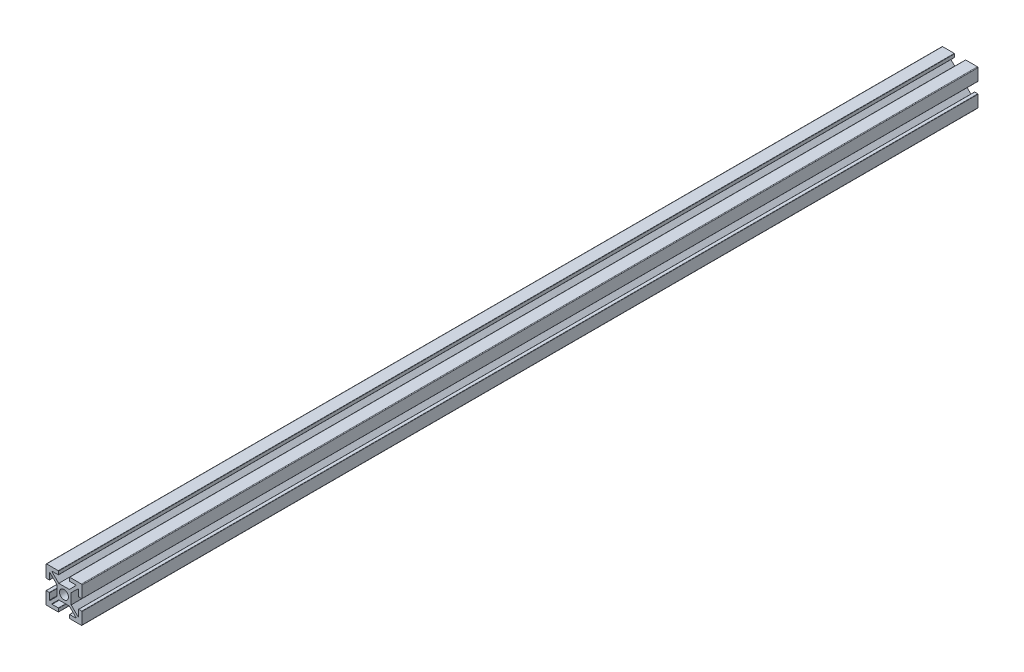
SolidWorks part; units mm, degrees
ref_plane "Front Plane" through (0, 0, 0) normal (0, 0, 1) x (1, 0, 0)
ref_plane "Top Plane" through (0, 0, 0) normal (0, 1, 0) x (1, 0, 0)
ref_plane "Right Plane" through (0, 0, 0) normal (1, 0, 0) x (0, 0, -1)
sketch "Sketch1" plane through (0, 0, 0) normal (0, 0, 1) x (1, 0, 0)
  line L0 (-7.4274, 2.1557) -> (-5.7274, 2.1557)
  line L1 (-0.7274, 9.1557) -> (-7.2274, 9.1557)
  line L2 (-7.5774, 2.3057) -> (-7.5774, 8.8057)
  line L3 (5.4021, 3.1557) -> (-0.4643, 3.1557)
  line L4 (-1.5311, -3.7897) -> (-1.5311, 2.1011)
  line L5 (-5.5774, 2.3057) -> (-5.5774, 5.7419)
  line L6 (-4.1455, 7.1557) -> (-0.7274, 7.1557)
  line L7 (-0.5774, 7.3057) -> (-0.5774, 9.0057)
  line L8 (-5.5774, 7.1557) -> (-1.5311, 3.1557) construction
  line L9 (-5.3219, 5.8486) -> (-1.5311, 2.1011)
  line L10 (-4.2509, 6.899) -> (-0.4643, 3.1557)
  line L11 (10.5152, 7.1557) -> (6.4689, 3.1557) construction
  line L12 (2.4689, -0.8443) -> (2.4689, 10.8443) construction
  line L13 (2.4689, -0.8443) -> (-12.5152, -0.8443) construction
  line L14 (9.1887, 6.899) -> (5.4021, 3.1557)
  line L15 (10.2598, 5.8486) -> (6.4689, 2.1011)
  line L16 (5.5152, 7.3057) -> (5.5152, 9.0057)
  line L17 (9.0833, 7.1557) -> (5.6652, 7.1557)
  line L18 (10.5152, 2.3057) -> (10.5152, 5.7419)
  line L19 (6.4689, -3.7897) -> (6.4689, 2.1011)
  line L20 (12.5152, 2.3057) -> (12.5152, 8.8057)
  line L21 (5.6652, 9.1557) -> (12.1652, 9.1557)
  line L22 (12.3652, 2.1557) -> (10.6652, 2.1557)
  line L23 (10.5152, -8.8443) -> (6.4689, -4.8443) construction
  line L24 (-5.5774, -8.8443) -> (-1.5311, -4.8443) construction
  line L25 (12.3652, -3.8443) -> (10.6652, -3.8443)
  line L26 (5.6652, -10.8443) -> (12.1652, -10.8443)
  line L27 (12.5152, -3.9943) -> (12.5152, -10.4943)
  line L28 (10.5152, -3.9943) -> (10.5152, -7.4305)
  line L29 (9.0833, -8.8443) -> (5.6652, -8.8443)
  line L30 (5.5152, -8.9943) -> (5.5152, -10.6943)
  line L31 (10.2598, -7.5372) -> (6.4689, -3.7897)
  line L32 (9.1887, -8.5876) -> (5.4021, -4.8443)
  line L33 (-4.2509, -8.5876) -> (-0.4643, -4.8443)
  line L34 (-5.3219, -7.5372) -> (-1.5311, -3.7897)
  line L35 (-0.5774, -8.9943) -> (-0.5774, -10.6943)
  line L36 (-4.1455, -8.8443) -> (-0.7274, -8.8443)
  line L37 (-5.5774, -3.9943) -> (-5.5774, -7.4305)
  line L38 (5.4021, -4.8443) -> (-0.4643, -4.8443)
  line L39 (-7.5774, -3.9943) -> (-7.5774, -10.4943)
  line L40 (-0.7274, -10.8443) -> (-7.2274, -10.8443)
  line L41 (-7.4274, -3.8443) -> (-5.7274, -3.8443)
  circle A0 centre (2.4689, -0.8443) radius 2.5
  arc A1 (-7.5774, 8.8057) -> (-7.2274, 9.1557) centre (-7.2274, 8.8057) cw
  arc A2 (-7.4274, 2.1557) -> (-7.5774, 2.3057) centre (-7.4274, 2.3057) cw
  arc A3 (-5.7274, 2.1557) -> (-5.5774, 2.3057) centre (-5.7274, 2.3057) ccw
  arc A4 (-0.7274, 9.1557) -> (-0.5774, 9.0057) centre (-0.7274, 9.0057) cw
  arc A5 (-0.7274, 7.1557) -> (-0.5774, 7.3057) centre (-0.7274, 7.3057) ccw
  arc A6 (-4.2509, 6.899) -> (-4.1455, 7.1557) centre (-4.1455, 7.0057) cw
  arc A7 (-5.3219, 5.8486) -> (-5.5774, 5.7419) centre (-5.4274, 5.7419) ccw
  arc A8 (10.2598, 5.8486) -> (10.5152, 5.7419) centre (10.3652, 5.7419) cw
  arc A9 (9.1887, 6.899) -> (9.0833, 7.1557) centre (9.0833, 7.0057) ccw
  arc A10 (5.6652, 7.1557) -> (5.5152, 7.3057) centre (5.6652, 7.3057) cw
  arc A11 (5.6652, 9.1557) -> (5.5152, 9.0057) centre (5.6652, 9.0057) ccw
  arc A12 (10.6652, 2.1557) -> (10.5152, 2.3057) centre (10.6652, 2.3057) cw
  arc A13 (12.3652, 2.1557) -> (12.5152, 2.3057) centre (12.3652, 2.3057) ccw
  arc A14 (12.5152, 8.8057) -> (12.1652, 9.1557) centre (12.1652, 8.8057) ccw
  arc A15 (12.5152, -10.4943) -> (12.1652, -10.8443) centre (12.1652, -10.4943) cw
  arc A16 (12.3652, -3.8443) -> (12.5152, -3.9943) centre (12.3652, -3.9943) cw
  arc A17 (10.6652, -3.8443) -> (10.5152, -3.9943) centre (10.6652, -3.9943) ccw
  arc A18 (5.6652, -10.8443) -> (5.5152, -10.6943) centre (5.6652, -10.6943) cw
  arc A19 (5.6652, -8.8443) -> (5.5152, -8.9943) centre (5.6652, -8.9943) ccw
  arc A20 (9.1887, -8.5876) -> (9.0833, -8.8443) centre (9.0833, -8.6943) cw
  arc A21 (10.2598, -7.5372) -> (10.5152, -7.4305) centre (10.3652, -7.4305) ccw
  arc A22 (-5.3219, -7.5372) -> (-5.5774, -7.4305) centre (-5.4274, -7.4305) cw
  arc A23 (-4.2509, -8.5876) -> (-4.1455, -8.8443) centre (-4.1455, -8.6943) ccw
  arc A24 (-0.7274, -8.8443) -> (-0.5774, -8.9943) centre (-0.7274, -8.9943) cw
  arc A25 (-0.7274, -10.8443) -> (-0.5774, -10.6943) centre (-0.7274, -10.6943) ccw
  arc A26 (-5.7274, -3.8443) -> (-5.5774, -3.9943) centre (-5.7274, -3.9943) cw
  arc A27 (-7.4274, -3.8443) -> (-7.5774, -3.9943) centre (-7.4274, -3.9943) ccw
  arc A28 (-7.5774, -10.4943) -> (-7.2274, -10.8443) centre (-7.2274, -10.4943) ccw
  point P27 (5.5152, 7.1557)
  point P28 (12.5152, -10.8443)
  point P47 (6.4689, -0.8443)
  point P57 (2.4689, 3.1557)
  point P59 (5.5152, 9.1557)
  point P60 (10.5152, 2.1557)
  point P61 (12.5152, 2.1557)
  point P62 (12.5152, 9.1557)
  point P112 (-1.5311, -0.8443)
  point P113 (12.5152, -3.8443)
  point P114 (10.5152, -3.8443)
  point P115 (5.5152, -10.8443)
  point P116 (2.4689, -4.8443)
  point P117 (-0.5774, -8.8443)
  point P118 (-0.5774, -10.8443)
  point P119 (-5.5774, -3.8443)
  point P120 (5.5152, -8.8443)
  point P121 (-7.5774, -3.8443)
  point P122 (-7.5774, -10.8443)
  dimension "D3" = 0.35
  dimension "D4" = 0.15
  dimension "D5" = 0.15
  dimension "D6" = 0.15
  dimension "D7" = 0.15
  dimension "D8" = 0.15
  dimension "D9" = 0.15
  dimension "D1" = 0.75
  dimension "D2" = 0.75
extrude "Boss-Extrude1" add sketch "Sketch1" along normal blind 500
